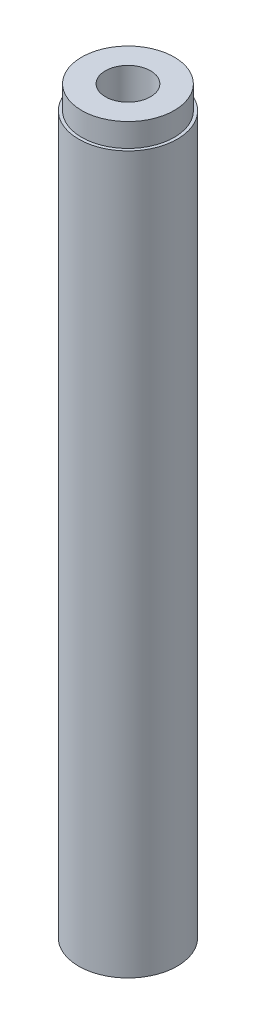
SolidWorks part; units mm, degrees
ref_plane "Front Plane" through (0, 0, 0) normal (0, 0, 1) x (1, 0, 0)
ref_plane "Top Plane" through (0, 0, 0) normal (0, 1, 0) x (1, 0, 0)
ref_plane "Right Plane" through (0, 0, 0) normal (1, 0, 0) x (0, 0, -1)
sketch "Sketch1" plane through (0, 0, 0) normal (0, 1, 0) x (1, 0, 0)
  circle A0 centre (0, 0) radius 6.55
  circle A1 centre (0, 0) radius 3
  dimension "D1" = 13.1
  dimension "D2" = 6
extrude "Boss-Extrude1" add sketch "Sketch1" along normal blind 98.3
sketch "Sketch2" plane through (0, 98.3, 0) normal (0, 1, 0) x (1, 0, 0)
  circle A0 centre (0, 0) radius 6.15
  circle A1 centre (0, 0) radius 6.55 construction
  circle A2 centre (0, 0) radius 6.55
  dimension "D1" = 12.3
extrude "Cut-Extrude1" cut sketch "Sketch2" against normal blind 3.1 contours A2 | A0
